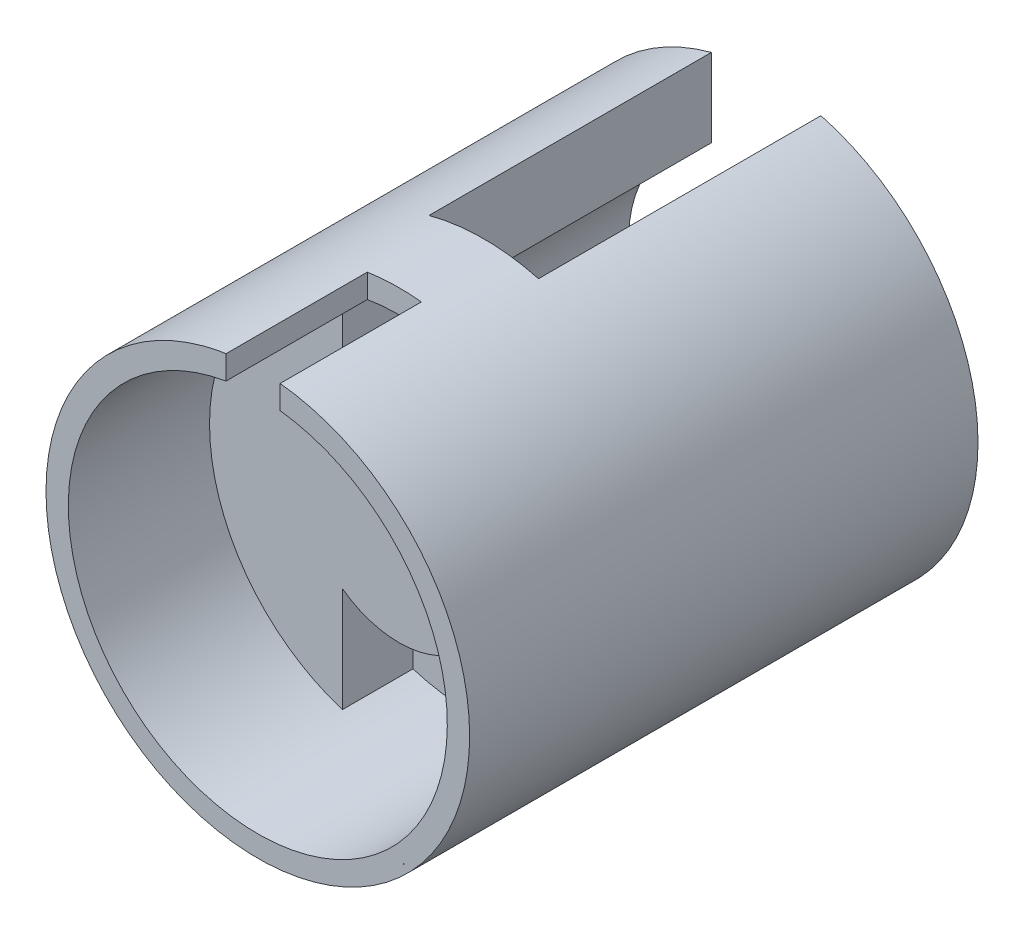
SolidWorks part; units mm, degrees
ref_plane "Front Plane" through (0, 0, 0) normal (0, 0, 1) x (1, 0, 0)
ref_plane "Top Plane" through (0, 0, 0) normal (0, 1, 0) x (1, 0, 0)
ref_plane "Right Plane" through (0, 0, 0) normal (1, 0, 0) x (0, 0, -1)
sketch "Sketch1" plane through (0, 0, 0) normal (0, 0, 1) x (1, 0, 0)
  line L1 (4.1647, 15.6233) -> (4.1647, 8.3534) construction
  line L2 (-3.8584, 8.3534) -> (-3.8584, 15.6233)
  line L3 (4.1647, 8.3534) -> (4.1647, 15.6233)
  line L4 (-3.8584, -2.56) -> (-3.8584, -9.9872)
  line L5 (4.1647, -2.56) -> (4.1647, -9.9872)
  line L6 (-3.8584, 15.6233) -> (-3.8584, 8.3534) construction
  line L7 (-3.8584, -2.56) -> (-3.8584, -9.9872) construction
  line L8 (4.1647, -2.56) -> (4.1647, -9.9872) construction
  circle A0 centre (0.1532, 2.8967) radius 15
  arc A3 (-3.8584, 15.6233) -> (4.1647, 15.6233) centre (0.1532, 2.8967) cw
  arc A6 (-3.8584, -9.9872) -> (4.1647, -9.9872) centre (0.1532, 2.8181) ccw
  arc A7 (4.1647, 15.6233) -> (-3.8584, 15.6233) centre (0.1532, 2.8181) ccw
  arc A8 (-3.8584, -2.56) -> (4.1647, -2.56) centre (0.1532, 2.8967) ccw
  arc A9 (4.1647, 8.3534) -> (-3.8584, 8.3534) centre (0.1532, 2.8967) ccw
  arc A10 (-3.8584, -9.9872) -> (4.1647, -9.9872) centre (0.1532, 2.8181) ccw
  dimension "D1" = 30
  dimension "D3" = 6.5713
  dimension "D4" = 0.0786
  dimension "D6" = 6.7726
  dimension "D7" = 10.9134
  dimension "D2" = 8.023
  dimension "D5" = 8.023
extrude "Boss-Extrude2" add sketch "Sketch1" along normal blind 5
sketch "Sketch10" plane through (0, 0, 5) normal (0, 0, 1) x (1, 0, 0)
  line L0 (-2.0941, 17.7274) -> (-2.0941, 16.0475)
  line L2 (1.7342, 16.1435) -> (1.7342, 17.8132)
  circle A0 centre (10.4918, -7.2762) radius 0.0267
  arc A1 (-2.0941, 16.0475) -> (1.7342, 16.1435) centre (0.1532, 2.8181) ccw
  circle A2 centre (0.1532, 2.8967) radius 15 construction
  circle A3 centre (0.1532, 2.8967) radius 15 construction
  circle M2 centre (0.1532, 2.8967) radius 15
  arc M3 (-3.8584, 15.6233) -> (4.1647, 15.6233) centre (0.1532, 2.8181) cw
  arc M7 (4.1647, -9.9872) -> (-3.8584, -9.9872) centre (0.1532, 2.8181) cw
  dimension "D1" = 3.8284
  dimension "D2" = 1.8145
extrude "Boss-Extrude10" add sketch "Sketch10" along normal blind 10 contours A1 L0 L2 A0 M3 M2 M7
sketch "Sketch11" plane through (0, 0, 0) normal (0, 0, -1) x (-1, 0, 0)
  circle A0 centre (-0.1532, -12.045) radius 0.0583
sketch "Sketch12" plane through (0, 0, 0) normal (0, 0, -1) x (-1, 0, 0)
  line L0 (-15.1532, 2.8967) -> (14.8468, 2.8967) construction
  circle A0 centre (-0.1532, 2.8967) radius 15 construction
  circle A1 centre (-0.1532, 2.8967) radius 15
extrude "Boss-Extrude13" add sketch "Sketch12" along normal blind 1
sketch "Sketch13" plane through (0, 0, -1) normal (0, 0, -1) x (-1, 0, 0)
  line L0 (-15.1532, 2.8967) -> (14.8468, 2.8967) construction
  line L3 (-4.032, 11.8419) -> (-4.032, 17.3865)
  line L4 (-0.1532, 17.8967) -> (-0.1532, -12.045) construction
  line L5 (3.7257, 11.8419) -> (3.7257, 17.3865)
  line L6 (-4.032, 17.3865) -> (3.7257, 17.3865) construction
  circle A0 centre (-0.1532, 2.8967) radius 15 construction
  circle A1 centre (-0.1532, 2.8967) radius 9.75
  circle M8 centre (-0.1532, 2.8967) radius 15
  dimension "D1" = 7.7578
  dimension "D2" = 19.5
extrude "Boss-Extrude14" add sketch "Sketch13" along normal blind 20 contours A1 L3 L5 M8
